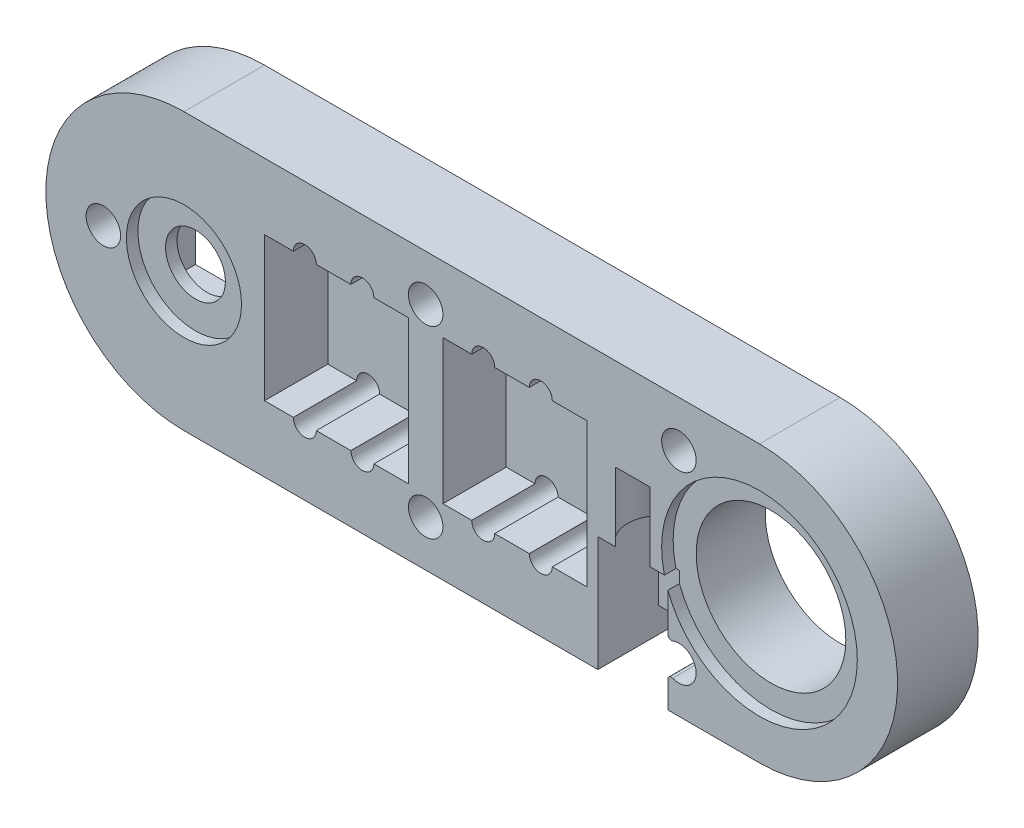
SolidWorks part; units mm, degrees
ref_plane "Спереди" through (0, 0, 0) normal (0, 0, 1) x (1, 0, 0)
ref_plane "Сверху" through (0, 0, 0) normal (0, 1, 0) x (1, 0, 0)
ref_plane "Справа" through (0, 0, 0) normal (1, 0, 0) x (0, 0, -1)
other "Configuration Table"
sketch "Эскиз1" plane through (0, 0, 0) normal (0, 0, 1) x (1, 0, 0)
  line L0 (0, -9.9) -> (50, -9.9) construction
  line L1 (0, 0) -> (50, 0)
  line L3 (0, -19.8) -> (50, -19.8)
  arc A4 (50, -19.8) -> (50, 0) centre (50, -9.9) ccw
  arc A5 (0, 0) -> (0, -19.8) centre (0, -9.9) ccw
  point P9 (0, 0)
  point P12 (50, -19.8)
  point P15 (50, 4.2)
  dimension "D1" = 24
  dimension "D2" = 50
extrude "Бобышка-Вытянуть1" add sketch "Эскиз1" along normal blind 7
sketch "Эскиз4" plane through (0, 0, 7) normal (0, 0, 1) x (1, 0, 0)
  line L1 (7, -3.65) -> (19.5, -3.65)
  line L2 (7, -3.65) -> (7, -16.15)
  line L3 (7, -16.15) -> (19.5, -16.15)
  line L4 (19.5, -3.65) -> (19.5, -16.15)
  line L5 (22.5, -3.65) -> (35, -3.65)
  line L6 (22.5, -3.65) -> (22.5, -16.15)
  line L7 (22.5, -16.15) -> (35, -16.15)
  line L8 (35, -3.65) -> (35, -16.15)
  line L11 (-9.9, -9.9) -> (59.9, -9.9) construction
  arc A0 (0, 0) -> (0, -19.8) centre (0, -9.9) ccw construction
  arc A1 (50, -19.8) -> (50, 0) centre (50, -9.9) ccw construction
  dimension "D1" = 12.5
  dimension "D2" = 12.5
  dimension "D3" = 12.5
  dimension "D4" = 12.5
  dimension "D5" = 6.25
  dimension "D6" = 7
  dimension "D7" = 3
extrude "Вырез-Вытянуть1" cut sketch "Эскиз4" against normal blind 5.5
sketch "Эскиз5" plane through (0, 0, 7) normal (0, 0, 1) x (1, 0, 0)
  circle A0 centre (0, -9.9) radius 2.6
  circle A1 centre (50, -9.9) radius 6.5
  dimension "D1" = 5.2
  dimension "D2" = 13
  dimension "D3" = 50
extrude "Вырез-Вытянуть2" cut sketch "Эскиз5" against normal through all
sketch "Эскиз6" plane through (0, 0, 7) normal (0, 0, 1) x (1, 0, 0)
  line L0 (19.5, -3.65) -> (7, -3.65) construction
  line L1 (35, -3.65) -> (22.5, -3.65) construction
  line L2 (7, -16.15) -> (19.5, -16.15) construction
  line L3 (22.5, -16.15) -> (35, -16.15) construction
  line L4 (7, -3.65) -> (7, -16.15) construction
  line L6 (22.5, -3.65) -> (22.5, -16.15) construction
  circle A0 centre (10.5, -3.65) radius 1
  circle A1 centre (15.5, -3.65) radius 1
  circle A2 centre (26, -3.65) radius 1
  circle A3 centre (31, -3.65) radius 1
  circle A4 centre (10.5, -16.15) radius 1
  circle A5 centre (15.5, -16.15) radius 1
  circle A6 centre (26, -16.15) radius 1
  circle A7 centre (31, -16.15) radius 1
  dimension "D1" = 2
  dimension "D2" = 3.5
  dimension "D3" = 5
  dimension "D4" = 3.5
  dimension "D5" = 5
extrude "Вырез-Вытянуть3" cut sketch "Эскиз6" against normal through all
sketch "Эскиз7" plane through (0, 0, 7) normal (0, 0, 1) x (1, 0, 0)
  circle A0 centre (40, -1.9) radius 1.55
  circle A1 centre (40, -17.9) radius 1.55
  circle A2 centre (7, -1.9) radius 1.55
  circle A3 centre (7, -17.9) radius 1.55
  circle A4 centre (0, -9.9) radius 2.6 construction
  circle A5 centre (50, -9.9) radius 6.5 construction
  dimension "D1" = 3.1
  dimension "D2" = 7
  dimension "D3" = 10
  dimension "D4" = 8
  dimension "D5" = 8
extrude "Вырез-Вытянуть4" [suppressed] cut sketch "Эскиз7" against normal blind 10
sketch "Эскиз8" plane through (0, 0, 7) normal (0, 0, 1) x (1, 0, 0)
  line L0 (0, -9.9) -> (50, -9.9) construction
  line L1 (0, -0.2094) -> (50, -0.2094)
  line L2 (0, -19.5906) -> (50, -19.5906)
  line L3 (0, -9.9) -> (50, -9.9) construction
  line L4 (0, 2.1) -> (50, 2.1)
  line L5 (0, -21.9) -> (50, -21.9)
  arc A0 (0, -0.2094) -> (0, -19.5906) centre (0, -9.9) ccw
  arc A1 (50, -19.5906) -> (50, -0.2094) centre (50, -9.9) ccw
  arc A2 (0, 2.1) -> (0, -21.9) centre (0, -9.9) ccw
  arc A3 (50, -21.9) -> (50, 2.1) centre (50, -9.9) ccw
  point P4 (25, -9.9)
  point P9 (25, -9.9)
  dimension "D1" = 24
extrude "Бобышка-Вытянуть2" add sketch "Эскиз8" against normal blind 7
sketch "Эскиз9" plane through (0, 0, 0) normal (0, 0, -1) x (-1, 0, 0)
  line L1 (-6, -3.9) -> (6, -3.9)
  line L2 (-6, -3.9) -> (-6, -15.9)
  line L3 (-6, -15.9) -> (6, -15.9)
  line L4 (6, -3.9) -> (6, -15.9)
  line L5 (-6, -3.9) -> (6, -15.9) construction
  line L6 (-6, -15.9) -> (6, -3.9) construction
  point P0 (0, -9.9)
  dimension "D1" = 12
  dimension "D2" = 12
extrude "Вырез-Вытянуть5" cut sketch "Эскиз9" against normal blind 5
sketch "Эскиз10" plane through (0, -21.9, 0) normal (0, -1, 0) x (1, 0, 0)
  line L0 (50, 0) -> (50, 7) construction
  line L1 (0, 7) -> (50, 7) construction
  circle A0 centre (39, 4.7) radius 2.75
  dimension "D1" = 5.5
  dimension "D2" = 11
  dimension "D3" = 2.3
extrude "Вырез-Вытянуть6" cut sketch "Эскиз10" against normal blind 16
sketch "Эскиз11" plane through (0, -21.9, 0) normal (0, -1, 0) x (1, 0, 0)
  line L1 (35.9568, 7.6711) -> (42.0432, 7.6711)
  line L2 (35.9568, 7.6711) -> (35.9568, 1.7289)
  line L3 (35.9568, 1.7289) -> (42.0432, 1.7289)
  line L4 (42.0432, 7.6711) -> (42.0432, 1.7289)
  line L5 (35.9568, 7.6711) -> (42.0432, 1.7289) construction
  line L6 (35.9568, 1.7289) -> (42.0432, 7.6711) construction
  point P0 (39, 4.7)
extrude "Вырез-Вытянуть7" cut sketch "Эскиз11" against normal blind 10
sketch "Эскиз13" plane through (0, 0, 1.7289) normal (0, 0, 1) x (1, 0, 0)
  line L0 (42.0432, -21.9) -> (42.0432, -11.9) construction
  line L1 (35.9568, -21.9) -> (42.0432, -21.9)
  line L2 (35.9568, -21.9) -> (35.9568, -19.7093)
  line L3 (35.9568, -19.7093) -> (42.0432, -19.7093)
  line L4 (42.0432, -21.9) -> (42.0432, -19.7093)
extrude "Вырез-Вытянуть8" cut sketch "Эскиз13" against normal blind 10
sketch "Эскиз14" plane through (0, 0, 7) normal (0, 0, 1) x (1, 0, 0)
  circle A0 centre (21, -1.9) radius 1.5
  circle A1 centre (21, -17.9) radius 1.5
  circle A2 centre (0, -9.9) radius 2.6 construction
  circle A3 centre (43, -1.9) radius 1.5
  circle A4 centre (-7, -9.9858) radius 1.5
  circle A5 centre (43, -17.9) radius 1.5
  point P10 (0, 0)
  point P13 (0, 0)
  dimension "D1" = 3
  dimension "D2" = 3
  dimension "D3" = 8
  dimension "D5" = 21
  dimension "D6" = 3
  dimension "D7" = 3
  dimension "D9" = 43
  dimension "D10" = 3
  dimension "D4" = 16
  dimension "D8" = 7
extrude "Вырез-Вытянуть9" cut sketch "Эскиз14" against normal blind 10
fillet "Скругление1" radius 0.3 2 edges at (-6, -8.8677, 2.5) (-6, -11.1038, 2.5)
fillet "Скругление2" radius 0.3 2 edges at (42.0432, -19.0552, 4.3644) (42.0432, -16.7448, 4.3644)
sketch "Эскиз15" plane through (0, 0, 7) normal (0, 0, 1) x (1, 0, 0)
  circle A0 centre (0, -9.9) radius 5
  circle A1 centre (50, -9.9) radius 8.5
  dimension "D1" = 17
  dimension "D2" = 10
extrude "Вырез-Вытянуть10" cut sketch "Эскиз15" against normal blind 1
